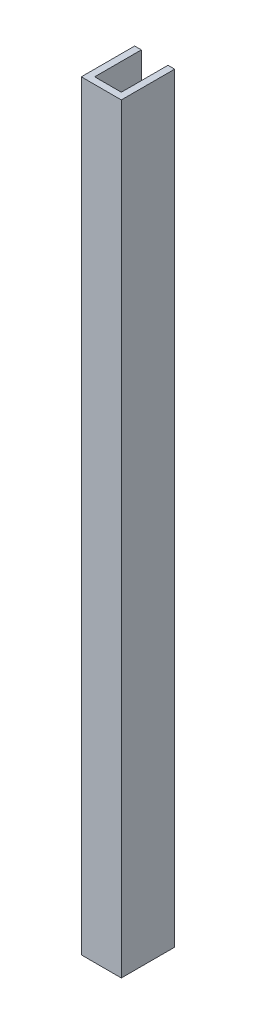
SolidWorks part; units mm, degrees
material "1060 Alloy"
ref_plane "Front Plane" through (0, 0, 0) normal (0, 0, 1) x (1, 0, 0)
ref_plane "Top Plane" through (0, 0, 0) normal (0, 1, 0) x (1, 0, 0)
ref_plane "Right Plane" through (0, 0, 0) normal (1, 0, 0) x (0, 0, -1)
sketch "Sketch1" plane through (0, 0, 0) normal (0, 1, 0) x (1, 0, 0)
  line L0 (0, 0) -> (19.05, 0)
  line L1 (19.05, 0) -> (19.05, 25.4)
  line L7 (0, 25.4) -> (0, 0)
  dimension "D1" = 25.4
  dimension "D2" = 19.05
  dimension "D3" = 25.4
extrude "Extrude-Thin1" add sketch "Sketch1" along normal blind 361.95 thin thin type one direction reverse wall 3.175
